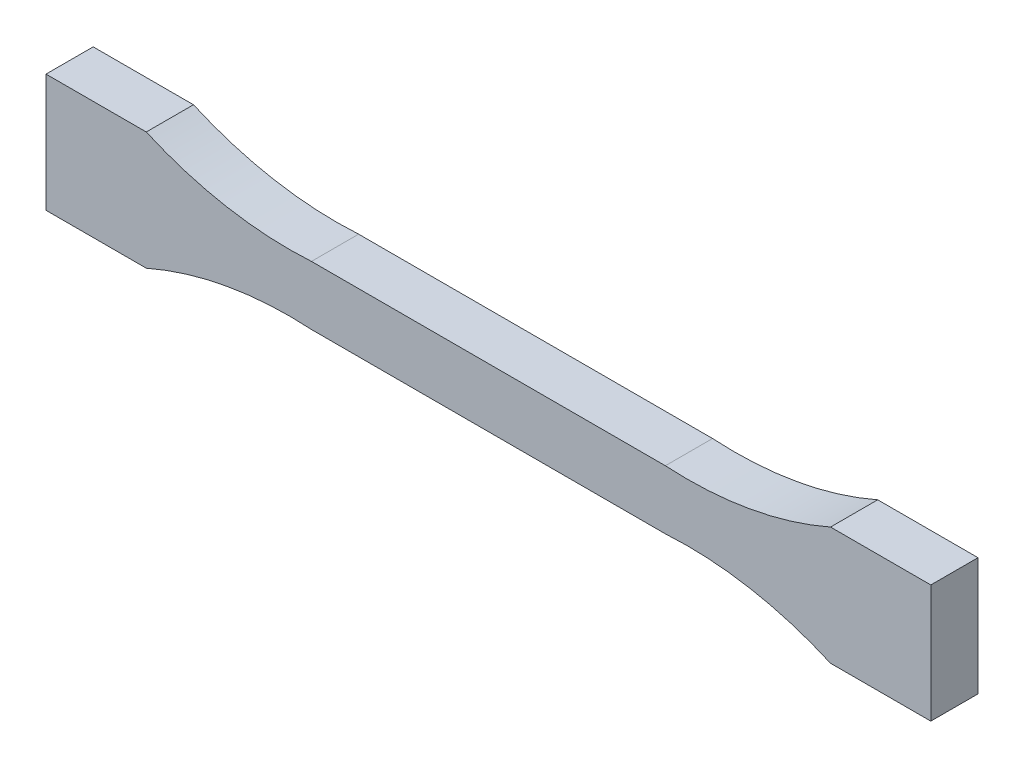
SolidWorks part; units mm, degrees
ref_plane "Front Plane" through (0, 0, 0) normal (0, 0, 1) x (1, 0, 0)
ref_plane "Top Plane" through (0, 0, 0) normal (0, 1, 0) x (1, 0, 0)
ref_plane "Right Plane" through (0, 0, 0) normal (1, 0, 0) x (0, 0, -1)
sketch "Sketch1" plane through (0, 0, 0) normal (0, 0, 1) x (1, 0, 0)
  line L1 (-15, 0) -> (15, 0)
  line L3 (-15, 5) -> (15, 5)
  line L9 (29, 7.5) -> (37.5, 7.5)
  line L10 (29, -2.5) -> (37.5, -2.5)
  line L11 (37.5, 7.5) -> (37.5, -2.5)
  line L12 (-29, -2.5) -> (-37.5, -2.5)
  line L13 (-37.5, 7.5) -> (-37.5, -2.5)
  line L14 (-29, 7.5) -> (-37.5, 7.5)
  arc A0 (15, 5) -> (29, 7.5) centre (16.8766, 34.9413) ccw
  arc A1 (29, -2.5) -> (15, 0) centre (16.8766, -29.9413) ccw
  arc A2 (-15, 5) -> (-29, 7.5) centre (-16.8766, 34.9413) cw
  arc A3 (-29, -2.5) -> (-15, 0) centre (-16.8766, -29.9413) cw
  dimension "D6" = 60
  dimension "D7" = 60
  dimension "D3" = 8.5
  dimension "D4" = 10
extrude "Boss-Extrude1" add sketch "Sketch1" along normal blind 4
